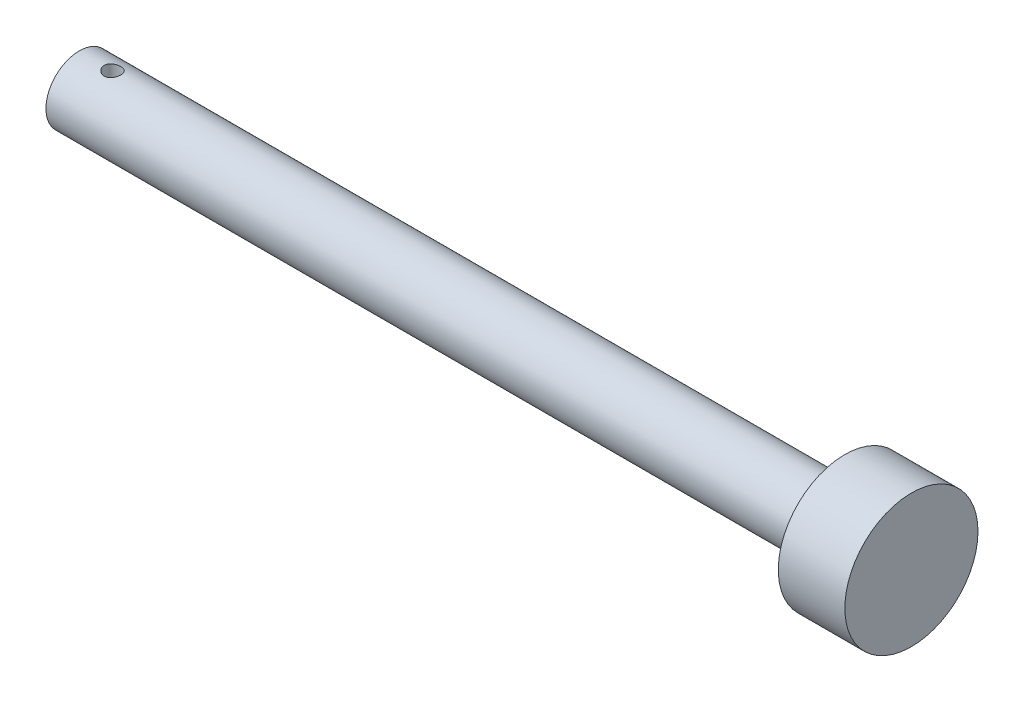
SolidWorks part; units mm, degrees
ref_plane "Front Plane" through (0, 0, 0) normal (0, 0, 1) x (1, 0, 0)
ref_plane "Top Plane" through (0, 0, 0) normal (0, 1, 0) x (1, 0, 0)
ref_plane "Right Plane" through (0, 0, 0) normal (1, 0, 0) x (0, 0, -1)
sketch "Sketch1" plane through (0, 0, 0) normal (1, 0, 0) x (0, 0, -1)
  circle A0 centre (0, 0) radius 16
  dimension "D1" = 32
extrude "Boss-Extrude1" add sketch "Sketch1" along normal blind 16
sketch "Sketch2" plane through (16, 0, 0) normal (1, 0, 0) x (0, 0, -1)
  circle A0 centre (0, 0) radius 8
  dimension "D1" = 16
extrude "Boss-Extrude2" add sketch "Sketch2" against normal blind 200
sketch "Sketch3" plane through (0, 0, 0) normal (0, 1, 0) x (1, 0, 0)
  line L0 (-184, 8) -> (-184, -8) construction
  circle A0 centre (-176, 0) radius 2
  dimension "D2" = 4
  dimension "D1" = 8
extrude "Cut-Extrude2" cut sketch "Sketch3" against normal through all both and the other way through all
